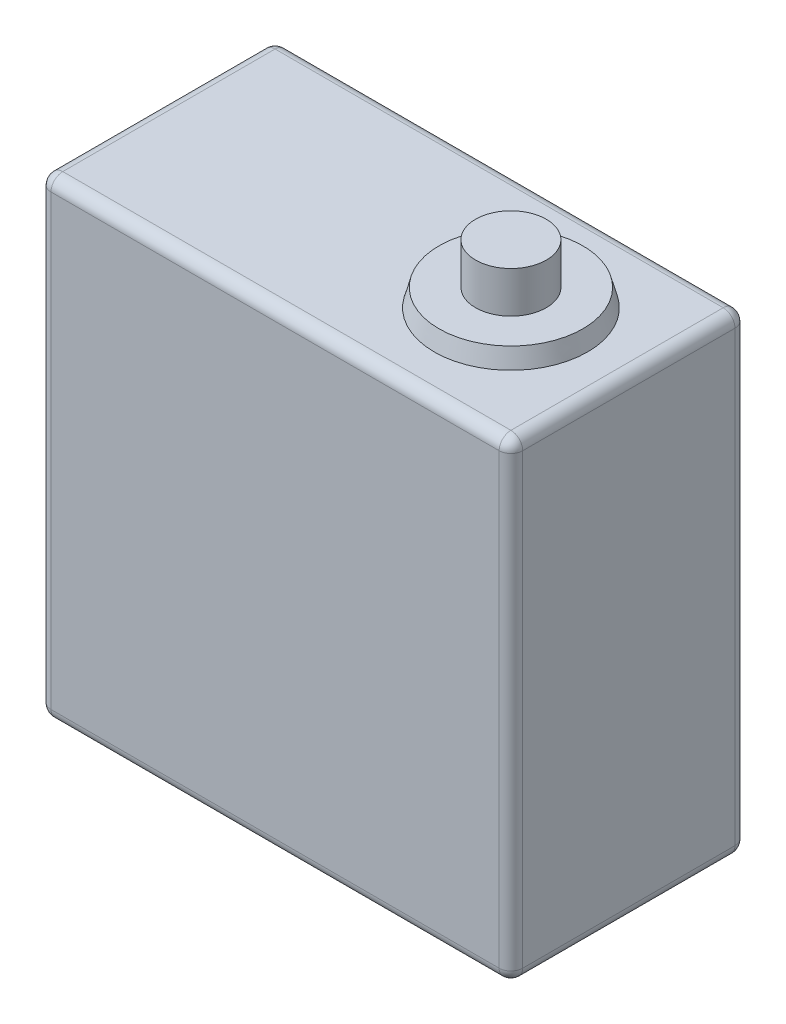
SolidWorks part; units mm, degrees
ref_plane "前视基准面" through (0, 0, 0) normal (0, 0, 1) x (1, 0, 0)
ref_plane "上视基准面" through (0, 0, 0) normal (0, 1, 0) x (1, 0, 0)
ref_plane "右视基准面" through (0, 0, 0) normal (1, 0, 0) x (0, 0, -1)
sketch "草图1" plane through (0, 0, 0) normal (0, 0, 1) x (1, 0, 0)
  line L1 (-20, 20) -> (20, 20)
  line L2 (-20, 20) -> (-20, -20)
  line L3 (-20, -20) -> (20, -20)
  line L4 (20, 20) -> (20, -20)
  line L5 (-20, 20) -> (20, -20) construction
  line L6 (-20, -20) -> (20, 20) construction
  point P0 (0, 0)
  dimension "D1" = 40
extrude "凸台-拉伸1" add sketch "草图1" along normal blind 20
fillet "圆角1" radius 1 12 edges at (20, 20, 10) (-20, 20, 10) (-20, -20, 10) (0, -20, 20) (-20, 0, 20) (0, 20, 20) (20, 0, 20) (-20, 0, 0) (0, 20, 0) (0, -20, 0) (20, 0, 0) (20, -20, 10)
sketch "草图2" plane through (0, 20, 0) normal (0, 1, 0) x (1, 0, 0)
  line L0 (10, -10) -> (20, -10)
  line L2 (20, -1) -> (20, -19) construction
  circle A0 centre (10, -10) radius 6.5
  point P2 (0, 0)
  point P3 (0, 0)
  point P5 (0, 0)
  point P6 (0, 0)
  point P7 (0, 0)
  point P10 (0, 0)
  dimension "D1" = 13
  dimension "D2" = 10
extrude "凸台-拉伸2" add sketch "草图2" along normal blind 1.5 draft 15 contours A0
sketch "草图3" plane through (0, 21.5, 0) normal (0, 1, 0) x (1, 0, 0)
  line L0 (10, -10) -> (20, -10)
  line L2 (20, -1) -> (20, -19) construction
  circle A0 centre (10, -10) radius 3
  point P2 (0, 0)
  point P4 (0, 0)
  point P7 (0, 0)
  dimension "D2" = 6
  dimension "D1" = 10
extrude "凸台-拉伸3" add sketch "草图3" along normal blind 3.5 contours A0
sketch "草图4" plane through (0, -20, 0) normal (0, -1, 0) x (1, 0, 0)
  line L0 (10, 10) -> (20, 10)
  line L2 (20, 19) -> (20, 1) construction
  circle A0 centre (10, 10) radius 6.5
  point P4 (0, 0)
  point P6 (0, 0)
  dimension "D1" = 13
  dimension "D2" = 10
extrude "凸台-拉伸4" add sketch "草图4" along normal blind 1.5 draft 15 contours A0
sketch "草图5" plane through (0, -21.5, 0) normal (0, -1, 0) x (1, 0, 0)
  line L0 (10, 10) -> (20, 10)
  line L2 (20, 19) -> (20, 1) construction
  circle A0 centre (10, 10) radius 3
  point P2 (0, 0)
  dimension "D2" = 6
  dimension "D1" = 10
extrude "凸台-拉伸5" add sketch "草图5" along normal blind 3.5 contours A0
